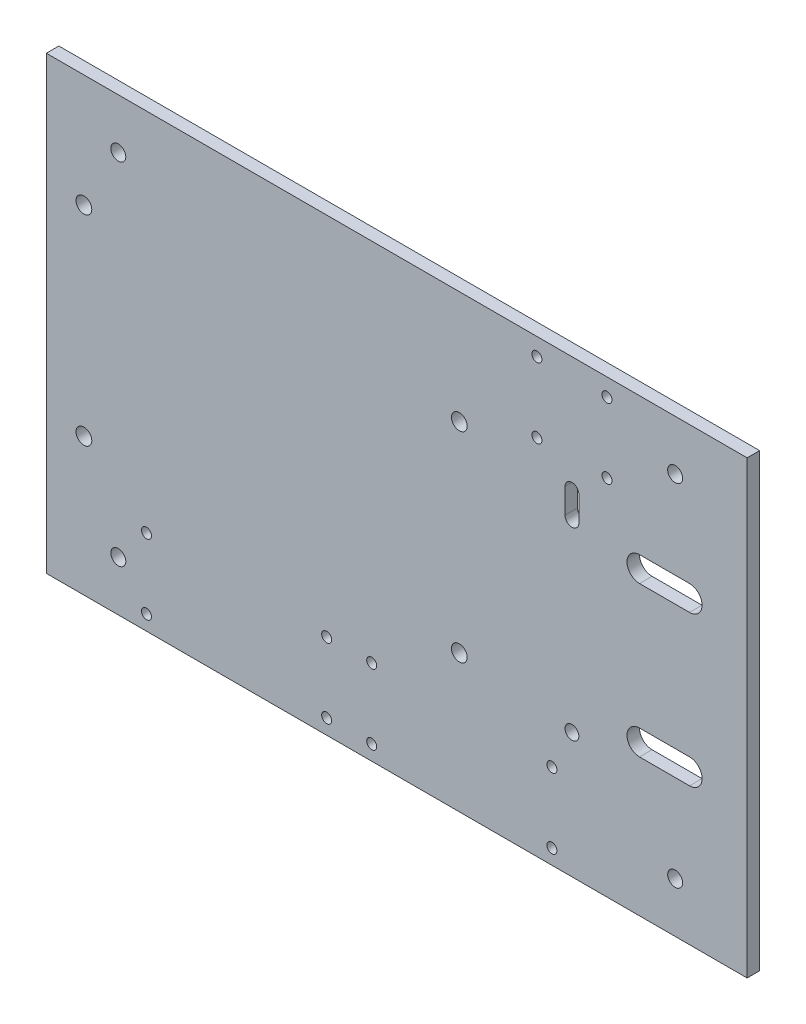
SolidWorks part; units mm, degrees
ref_plane "Front Plane" through (0, 0, 0) normal (0, 0, 1) x (1, 0, 0)
ref_plane "Top Plane" through (0, 0, 0) normal (0, 1, 0) x (1, 0, 0)
ref_plane "Right Plane" through (0, 0, 0) normal (1, 0, 0) x (0, 0, -1)
sketch "Sketch1" plane through (0, 0, 0) normal (0, 0, 1) x (1, 0, 0)
  line L1 (-88.9, 57.15) -> (88.9, 57.15)
  line L2 (-88.9, 57.15) -> (-88.9, -57.15)
  line L3 (-88.9, -57.15) -> (88.9, -57.15)
  line L4 (88.9, 57.15) -> (88.9, -57.15)
  line L5 (-88.9, 57.15) -> (88.9, -57.15) construction
  line L6 (-88.9, -57.15) -> (88.9, 57.15) construction
  point P0 (0, 0)
  dimension "D1" = 177.8
  dimension "D2" = 114.3
extrude "Boss-Extrude1" add sketch "Sketch1" along normal blind 3.175
sketch "Sketch8" plane through (0, 0, 3.175) normal (0, 0, 1) x (1, 0, 0)
  line L1 (-79.375, 28.575) -> (15.875, 28.575) construction
  line L2 (-79.375, 28.575) -> (-79.375, -22.225) construction
  line L3 (-79.375, -22.225) -> (15.875, -22.225) construction
  line L4 (15.875, 28.575) -> (15.875, -22.225) construction
  line L5 (-79.375, 28.575) -> (15.875, -22.225) construction
  line L6 (-79.375, -22.225) -> (15.875, 28.575) construction
  circle A0 centre (-79.375, 28.575) radius 2
  circle A1 centre (15.875, 28.575) radius 2
  circle A2 centre (15.875, -22.225) radius 2
  circle A3 centre (-79.375, -22.225) radius 2
  point P0 (-31.75, 3.175)
  dimension "D1" = 4
  dimension "D2" = 31.75
  dimension "D3" = 95.25
  dimension "D4" = 50.8
  dimension "D5" = 3.175
extrude "Cut-Extrude2" cut sketch "Sketch8" against normal through all
sketch "Sketch9" plane through (0, 0, 3.175) normal (0, 0, 1) x (1, 0, 0)
  line L0 (-88.9, 57.15) -> (-88.9, -57.15) construction
  line L1 (-63.5, -35.56) -> (-17.78, -35.56) construction
  line L2 (-63.5, -35.56) -> (-63.5, -53.34) construction
  line L3 (-63.5, -53.34) -> (-17.78, -53.34) construction
  line L4 (-17.78, -35.56) -> (-17.78, -53.34) construction
  line L5 (-63.5, -35.56) -> (-17.78, -53.34) construction
  line L6 (-63.5, -53.34) -> (-17.78, -35.56) construction
  circle A0 centre (-63.5, -35.56) radius 1.27
  circle A1 centre (-17.78, -35.56) radius 1.27
  circle A2 centre (-17.78, -53.34) radius 1.27
  circle A3 centre (-63.5, -53.34) radius 1.27
  point P0 (-40.64, -44.45)
  dimension "D1" = 2.54
  dimension "D2" = 45.72
  dimension "D3" = 17.78
  dimension "D4" = 44.45
  dimension "D5" = 25.4
extrude "Cut-Extrude3" cut sketch "Sketch9" against normal through all
pattern_linear "LPattern1" count 2 spacing 57.15 along (1, 0, 0) of "Cut-Extrude3"
sketch "Sketch10" plane through (0, 0, 3.175) normal (0, 0, 1) x (1, 0, 0)
  line L1 (35.56, 52.705) -> (53.34, 52.705) construction
  line L2 (35.56, 52.705) -> (35.56, 34.925) construction
  line L3 (35.56, 34.925) -> (53.34, 34.925) construction
  line L4 (53.34, 52.705) -> (53.34, 34.925) construction
  line L5 (35.56, 52.705) -> (53.34, 34.925) construction
  line L6 (35.56, 34.925) -> (53.34, 52.705) construction
  circle A0 centre (35.56, 52.705) radius 1.27
  circle A1 centre (53.34, 52.705) radius 1.27
  circle A2 centre (53.34, 34.925) radius 1.27
  circle A3 centre (35.56, 34.925) radius 1.27
  point P0 (44.45, 43.815)
  dimension "D5" = 2.54
  dimension "D1" = 17.78
  dimension "D2" = 17.78
  dimension "D3" = 44.45
  dimension "D4" = 34.925
extrude "Cut-Extrude4" cut sketch "Sketch10" against normal through all
sketch "Sketch11" plane through (0, 0, 3.175) normal (0, 0, 1) x (1, 0, 0)
  line L0 (-88.9, -57.15) -> (88.9, -57.15) construction
  line L3 (44.45, 21.425) -> (44.45, 27.775) construction
  line L4 (42.7, 21.425) -> (42.7, 27.775)
  line L5 (46.2, 21.425) -> (46.2, 27.775)
  line L6 (88.9, -57.15) -> (88.9, 57.15) construction
  arc A2 (42.7, 21.425) -> (46.2, 21.425) centre (44.45, 21.425) ccw
  arc A3 (46.2, 27.775) -> (42.7, 27.775) centre (44.45, 27.775) ccw
  circle A4 centre (44.45, -25.4) radius 1.75
  point P7 (44.45, 24.6)
  dimension "D4" = 6.35
  dimension "D3" = 50
  dimension "D5" = 31.75
  dimension "D2" = 3.5
  dimension "D1" = 3.5
  dimension "D6" = 44.45
extrude "Cut-Extrude5" cut sketch "Sketch11" against normal through all
hole_wizard "#6 Clearance Hole1" positions "Sketch14" profile "Sketch15" hole size "#6" standard "ANSI Inch"
sketch "Sketch14" plane through (0, 0, 0) normal (0, 0, -1) x (-1, 0, 0)
  point P22 (-70.6438, 44.45)
  point P24 (-70.6438, -44.45)
  dimension "D1" = 70.6437
  dimension "D2" = 44.45
  dimension "D3" = 44.45
sketch "Sketch15" plane through (70.6438, 44.45, 0) normal (1, 0, 0) x (0, 1, 0)
  line L0 (0, 0) -> (0, 26.5408)
  line L1 (0, 26.5408) -> (1.8986, 25.4)
  line L2 (1.8986, 25.4) -> (1.8986, 0)
  line L5 (1.8986, 0) -> (0, 0)
  line L10 (0, 26.5408) -> (-1.8987, 25.4) construction
  line L11 (0, -6.35) -> (0, 107.95) construction
  dimension "Hole Dia." = 3.7973
  dimension "Hole Depth" = 25.4
  dimension "Drill Angle" = 118
sketch "Sketch16" plane through (0, 0, 0) normal (0, 0, -1) x (-1, 0, 0)
  line L0 (-74.295, 19.05) -> (-61.595, 19.05) construction
  line L1 (-74.295, 22.225) -> (-61.595, 22.225)
  line L2 (-74.295, 15.875) -> (-61.595, 15.875)
  arc A0 (-74.295, 22.225) -> (-74.295, 15.875) centre (-74.295, 19.05) ccw
  arc A1 (-61.595, 15.875) -> (-61.595, 22.225) centre (-61.595, 19.05) ccw
  point P2 (-67.945, 19.05)
  dimension "D2" = 12.7
  dimension "D1" = 6.35
  dimension "D3" = 19.05
  dimension "D4" = 67.945
extrude "Cut-Extrude6" cut sketch "Sketch16" against normal through all
mirror "Mirror4" about plane through (0, 0, 0) normal (0, 1, 0) of "Cut-Extrude6"
mirror "Mirror5" about plane through (0, 0, 0) normal (1, 0, 0) of "#6 Clearance Hole1"
